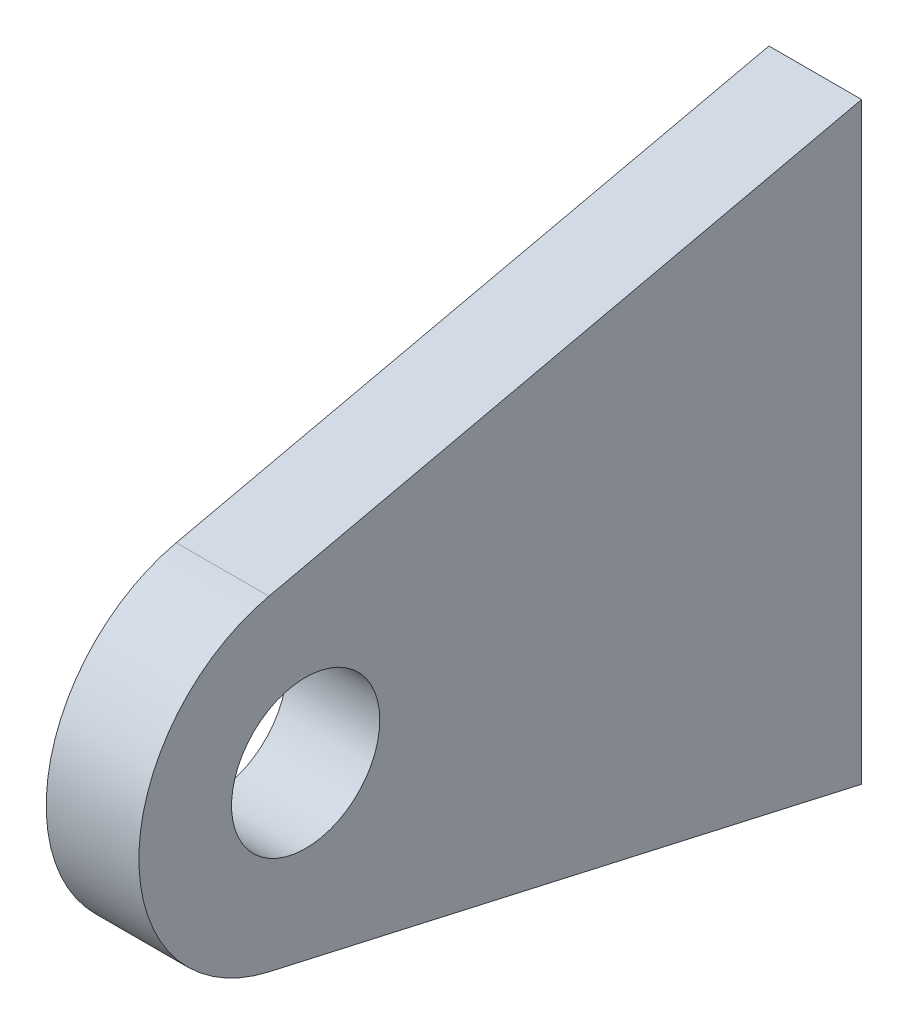
SolidWorks part; units mm, degrees
ref_plane "Front Plane" through (0, 0, 0) normal (1, 0, 0) x (0, 1, 0)
ref_plane "Top Plane" through (0, 0, 0) normal (0, 0, 1) x (0, 1, 0)
ref_plane "Right Plane" through (0, 0, 0) normal (0, 1, 0) x (-1, 0, 0)
sketch "Sketch1" plane through (0, 0, 0) normal (1, 0, 0) x (0, 1, 0)
  line L0 (-16, 0) -> (16, 0)
  line L1 (0, 0) -> (0, 30) construction
  line L2 (-16, 0) -> (-8.779, 31.9821)
  line L3 (16, 0) -> (8.779, 31.9821)
  circle A0 centre (0, 30) radius 4
  arc A1 (8.779, 31.9821) -> (-8.779, 31.9821) centre (0, 30) ccw
  arc A2 (-8.779, 31.9821) -> (0, 21) centre (0, 30) ccw construction
  circle A3 centre (0, 30) radius 9 construction
  arc A4 (0, 21) -> (8.779, 31.9821) centre (0, 30) ccw construction
  point P4 (0, 0)
  dimension "D3" = 8
  dimension "D1" = 32
  dimension "D2" = 30
  dimension "D4" = 5
extrude "Boss-Extrude1" add sketch "Sketch1" along normal mid plane 5
ref_point "Point1"
sketch3d "3DSketch2"
  line L0 (0, 0, 30) -> (0, 0, 0) construction
  line L1 (0, 0, 0) -> (0, 0, -5.875) construction
  line L2 (0, 0, -5.875) -> (-13.375, 0, -5.875) construction
  dimension "D1" = 5.875
  dimension "D2" = 13.375
